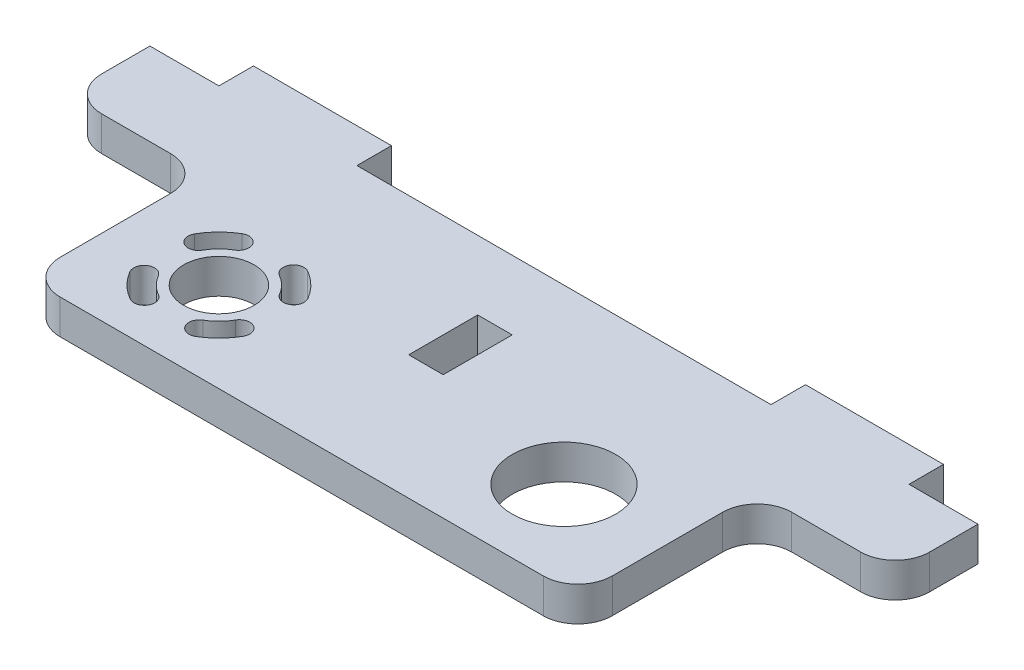
SolidWorks part; units mm, degrees
ref_plane "前视基准面" through (0, 0, 0) normal (0, 0, 1) x (1, 0, 0)
ref_plane "上视基准面" through (0, 0, 0) normal (0, 1, 0) x (1, 0, 0)
ref_plane "右视基准面" through (0, 0, 0) normal (1, 0, 0) x (0, 0, -1)
sketch "草图1" plane through (0, 0, 0) normal (0, 1, 0) x (1, 0, 0)
  line L0 (5, 0) -> (75, 0)
  line L1 (80, 5) -> (80, 21)
  line L2 (85, 26) -> (95, 26)
  line L3 (100, 31) -> (100, 38)
  line L4 (100, 38) -> (90, 38)
  line L5 (-20, 38) -> (-20, 31)
  line L6 (-15, 26) -> (-5, 26)
  line L7 (0, 21) -> (0, 5)
  line L8 (-23.2382, 13) -> (110.2759, 13) construction
  line L9 (-10, 38) -> (-20, 38)
  line L10 (70, 38) -> (10, 38)
  line L11 (-10, 38) -> (-10, 43)
  line L12 (11, 25.2979) -> (11, -2.3327) construction
  line L13 (-10, 43) -> (10, 43)
  line L14 (10, 38) -> (10, 43)
  line L15 (40, 53.221) -> (40, -9.5525) construction
  line L16 (70, 38) -> (70, 43)
  line L17 (70, 43) -> (90, 43)
  line L18 (90, 38) -> (90, 43)
  line L20 (37.5, 28) -> (42.5, 28)
  line L21 (37.5, 28) -> (37.5, 18)
  line L22 (37.5, 18) -> (42.5, 18)
  line L23 (42.5, 28) -> (42.5, 18)
  circle A0 centre (15, 13) radius 5.1
  circle A1 centre (65, 13) radius 7.5
  circle A2 centre (15, 13) radius 8 construction
  arc A3 (8.1163, 16.923) -> (11, 19.8392) centre (15, 13) cw construction
  arc A4 (10.2427, 21.134) -> (6.8131, 17.6656) centre (15, 13) ccw
  arc A5 (11.7573, 18.5444) -> (9.4195, 16.1803) centre (15, 13) ccw
  arc A6 (11.7573, 18.5444) -> (10.2427, 21.134) centre (11, 19.8392) ccw
  arc A7 (6.8131, 17.6656) -> (9.4195, 16.1803) centre (8.1163, 16.923) ccw
  arc A8 (18.923, 19.8837) -> (21.8392, 17) centre (15, 13) cw construction
  arc A9 (23.134, 17.7573) -> (19.6656, 21.1869) centre (15, 13) ccw
  arc A10 (20.5444, 16.2427) -> (18.1803, 18.5805) centre (15, 13) ccw
  arc A11 (20.5444, 16.2427) -> (23.134, 17.7573) centre (21.8392, 17) ccw
  arc A12 (19.6656, 21.1869) -> (18.1803, 18.5805) centre (18.923, 19.8837) ccw
  arc A13 (21.8837, 9.077) -> (19, 6.1608) centre (15, 13) cw construction
  arc A14 (19.7573, 4.866) -> (23.1869, 8.3344) centre (15, 13) ccw
  arc A15 (18.2427, 7.4556) -> (20.5805, 9.8197) centre (15, 13) ccw
  arc A16 (18.2427, 7.4556) -> (19.7573, 4.866) centre (19, 6.1608) ccw
  arc A17 (23.1869, 8.3344) -> (20.5805, 9.8197) centre (21.8837, 9.077) ccw
  arc A18 (11.077, 6.1163) -> (8.1608, 9) centre (15, 13) cw construction
  arc A19 (6.866, 8.2427) -> (10.3344, 4.8131) centre (15, 13) ccw
  arc A20 (9.4556, 9.7573) -> (11.8197, 7.4195) centre (15, 13) ccw
  arc A21 (9.4556, 9.7573) -> (6.866, 8.2427) centre (8.1608, 9) ccw
  arc A22 (10.3344, 4.8131) -> (11.8197, 7.4195) centre (11.077, 6.1163) ccw
  arc A23 (-20, 31) -> (-15, 26) centre (-15, 31) ccw
  arc A24 (95, 26) -> (100, 31) centre (95, 31) ccw
  arc A25 (75, 0) -> (80, 5) centre (75, 5) ccw
  arc A26 (5, 0) -> (0, 5) centre (5, 5) cw
  arc A27 (80, 21) -> (85, 26) centre (85, 21) cw
  arc A28 (-5, 26) -> (0, 21) centre (-5, 21) cw
  point P13 (20.5709, 18.6338)
  point P27 (20.6338, 7.4291)
  point P30 (9.3662, 18.5709)
  point P43 (9.4291, 7.3662)
  point P48 (15, 13)
  point P57 (-20, 26)
  point P58 (22.0906, 15.2472)
  point P61 (100, 26)
  point P64 (80, 0)
  point P67 (0, 0)
  point P70 (80, 26)
  point P73 (0, 26)
  dimension "D5" = 10.2
  dimension "D6" = 15
  dimension "D21" = 5
  dimension "D22" = 5
  dimension "D23" = 16
  dimension "D24" = 60
  dimension "D1" = 80
  dimension "D2" = 20
  dimension "D3" = 20
  dimension "D4" = 50
  dimension "D7" = 4
  dimension "D8" = 15
  dimension "D9" = 13
  dimension "D10" = 13
  dimension "D11" = 26
  dimension "D12" = 26
  dimension "D13" = 12
  dimension "D14" = 4
  dimension "D15" = 20
  dimension "D16" = 20
  dimension "D17" = 5
  dimension "D18" = 5
  dimension "D19" = 10
  dimension "D20" = 10
  dimension "D25" = 30
  dimension "D26" = 5
  dimension "D27" = 2.5
  dimension "D28" = 10
  dimension "D29" = 10
extrude "凸台-拉伸1" add sketch "草图1" along normal blind 5
